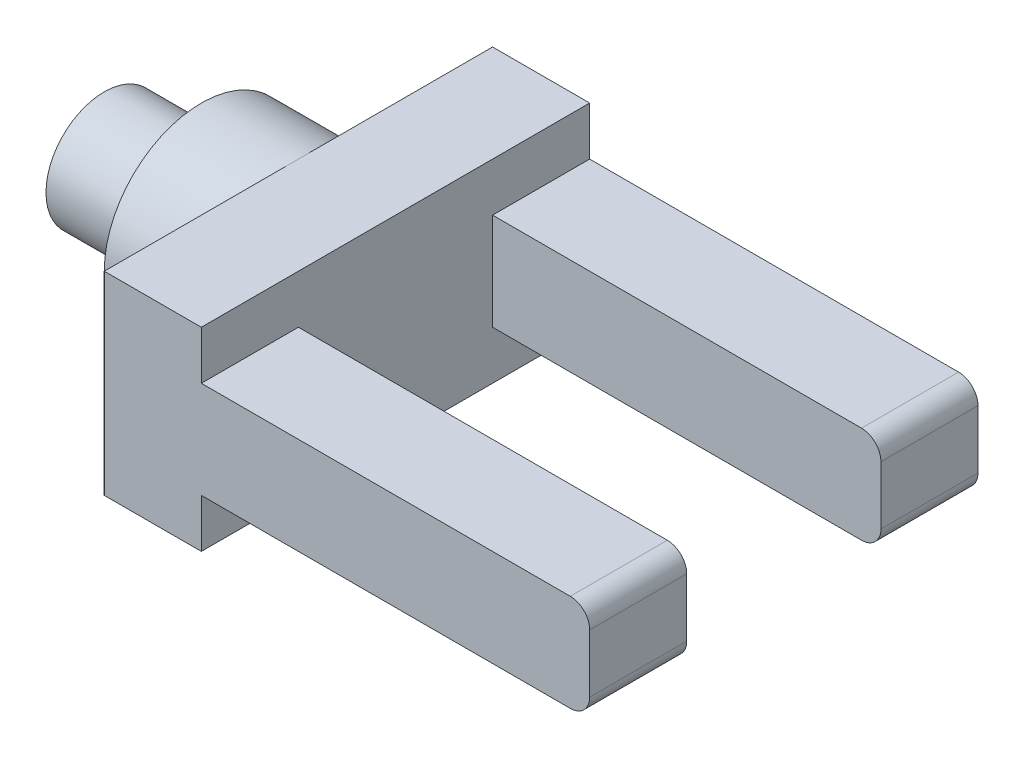
SolidWorks part; units mm, degrees
material "1023 Carbon Steel Sheet (SS)"
ref_plane "Front Plane" through (0, 0, 0) normal (0, 0, 1) x (1, 0, 0)
ref_plane "Top Plane" through (0, 0, 0) normal (0, 1, 0) x (1, 0, 0)
ref_plane "Right Plane" through (0, 0, 0) normal (1, 0, 0) x (0, 0, -1)
sketch "Sketch1" plane through (0, 0, 0) normal (1, 0, 0) x (0, 0, -1)
  circle A0 centre (0, 0) radius 10
extrude "Boss-Extrude1" add sketch "Sketch1" along normal blind 20
sketch "Sketch2" plane through (0, 0, 0) normal (-1, 0, 0) x (0, 0, 1)
  circle A0 centre (0, 0) radius 6
extrude "Cut-Extrude1" cut sketch "Sketch2" against normal blind 10 flip side to cut
sketch "Sketch4" plane through (20, 0, 0) normal (1, 0, 0) x (0, 0, -1)
  line L1 (-20, 10) -> (20, 10)
  line L2 (-20, 10) -> (-20, -10)
  line L3 (-20, -10) -> (20, -10)
  line L4 (20, 10) -> (20, -10)
  dimension "D1" = 40
  dimension "D2" = 20
extrude "Boss-Extrude2" add sketch "Sketch4" along normal blind 10
sketch "Sketch6" plane through (30, 0, 0) normal (1, 0, 0) x (0, 0, -1)
  line L0 (-20, 10) -> (-20, -10) construction
  line L1 (-20, 5) -> (-10, 5)
  line L2 (-20, 5) -> (-20, -5)
  line L3 (-20, -5) -> (-10, -5)
  line L4 (-10, 5) -> (-10, -5)
  line L5 (20, 10) -> (-20, 10) construction
  dimension "D1" = 10
  dimension "D2" = 10
  dimension "D3" = 0
  dimension "D4" = 5
extrude "Boss-Extrude3" add sketch "Sketch6" along normal blind 40
sketch "Sketch7" plane through (30, 0, 0) normal (1, 0, 0) x (0, 0, -1)
  line L0 (20, -10) -> (20, 10) construction
  line L9 (10, 5) -> (10, -5)
  line L10 (20, -5) -> (10, -5)
  line L11 (20, 5) -> (20, -5)
  line L12 (20, 5) -> (10, 5)
  dimension "D1" = 10
  dimension "D2" = 10
  dimension "D3" = 0
  dimension "D5" = 10
  dimension "D6" = 10
extrude "Boss-Extrude4" add sketch "Sketch7" along normal blind 40
fillet "Fillet1" radius 2 4 edges at (70, -5, -15) (70, 5, -15) (70, -5, 15) (70, 5, 15)
